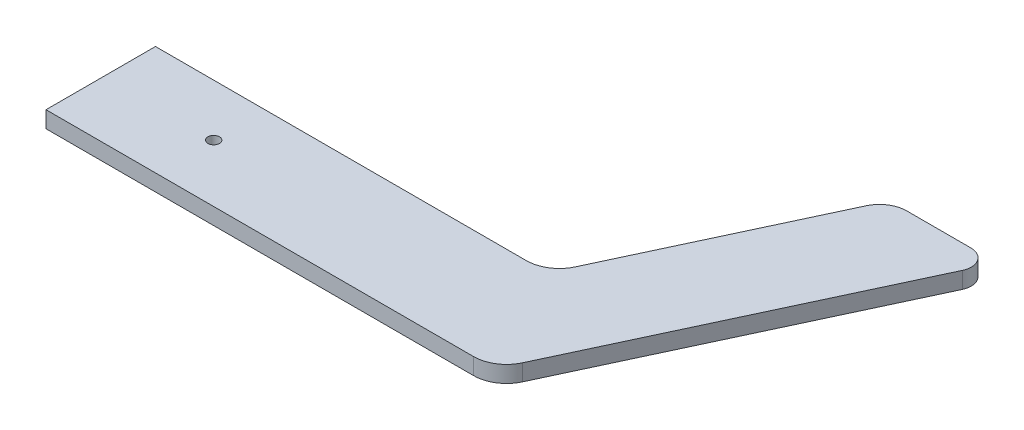
SolidWorks part; units mm, degrees
ref_plane "Front" through (0, 0, 0) normal (0, 0, 1) x (1, 0, 0)
ref_plane "Top" through (0, 0, 0) normal (0, 1, 0) x (1, 0, 0)
ref_plane "Right" through (0, 0, 0) normal (1, 0, 0) x (0, 0, -1)
sketch "Esboço1" plane through (0, 0, 0) normal (0, 1, 0) x (1, 0, 0)
  line L0 (-65, 19.8655) -> (-65, 0)
  line L1 (-65, 0) -> (0, 0)
  line L5 (2.2915, 19.8655) -> (-65, 19.8655)
  line L16 (0, 0) -> (12.5749, 0)
  line L18 (18.0127, 3.4643) -> (43.4106, 57.9302)
  line L19 (40.6917, 62.1981) -> (29.0117, 62.1981)
  line L20 (24.5194, 59.3361) -> (7.7293, 23.3298)
  circle A0 centre (-45, 10.4335) radius 1.05
  arc A7 (29.0117, 62.1981) -> (24.5194, 59.3361) centre (29.0117, 57.2413) ccw
  arc A8 (18.0127, 3.4643) -> (12.5749, 0) centre (12.5749, 6) cw
  arc A9 (7.7293, 23.3298) -> (2.2915, 19.8655) centre (2.2915, 25.8655) cw
  arc A10 (43.4106, 57.9302) -> (40.6917, 62.1981) centre (40.6917, 59.1981) ccw
  dimension "D4" = 2.1
  dimension "D5" = 245
  dimension "D6" = 3
  dimension "D2" = 245
  dimension "D7" = 6
  dimension "D8" = 6
  dimension "D1" = 65
  dimension "D3" = 20
extrude "Ressalto-extrusão1" add sketch "Esboço1" along normal blind 3
